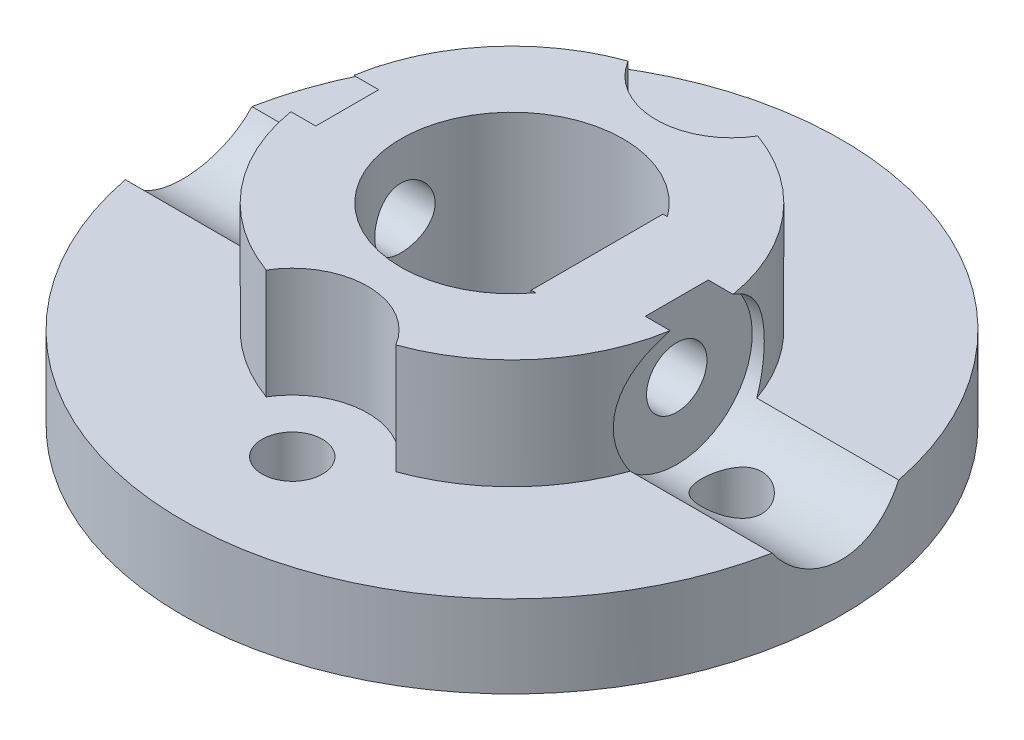
SolidWorks part; units mm, degrees
ref_plane "Front Plane" through (0, 0, 0) normal (0, 0, 1) x (1, 0, 0)
ref_plane "Top Plane" through (0, 0, 0) normal (0, 1, 0) x (1, 0, 0)
ref_plane "Right Plane" through (0, 0, 0) normal (1, 0, 0) x (0, 0, -1)
sketch "Stock_horn_drive_flange_profile" plane through (0, 0, 0) normal (0, 1, 0) x (1, 0, 0)
  circle A0 centre (0, 0) radius 12
  circle A1 centre (0, 0) radius 4.05
  dimension "D1" = 24
  dimension "D2" = 8.1
extrude "Stock_horn_drive_flange" add sketch "Stock_horn_drive_flange_profile" along normal blind 3 from offset 41
sketch "D_coupling_ring_profile" plane through (0, 0, 0) normal (0, 1, 0) x (1, 0, 0)
  circle A0 centre (0, 0) radius 7
  circle A1 centre (0, 0) radius 4.05
  dimension "D1" = 14
  dimension "D2" = 8.1
extrude "D_coupling_ring" add sketch "D_coupling_ring_profile" along normal blind 4 from offset 44
sketch "D_key_land_profile" plane through (0, 0, 0) normal (0, 1, 0) x (1, 0, 0)
  line L1 (3.1, -2.4) -> (6, -2.4)
  line L2 (3.1, -2.4) -> (3.1, 2.4)
  line L3 (3.1, 2.4) -> (6, 2.4)
  line L4 (6, -2.4) -> (6, 2.4)
  dimension "D1" = 2.9
  dimension "D2" = 4.8
extrude "D_key_land" add sketch "D_key_land_profile" along normal blind 4 from offset 44
sketch "Stock_horn_screws_profile" plane through (0, 0, 0) normal (0, 1, 0) x (1, 0, 0)
  circle A0 centre (-8, 0) radius 1.1
  circle A1 centre (8, 0) radius 1.1
  circle A2 centre (0, -8) radius 1.1
  circle A3 centre (0, 8) radius 1.1
  dimension "D1" = 2.2
  dimension "D2" = 2.2
  dimension "D3" = 2.2
  dimension "D4" = 2.2
extrude "Stock_horn_screws" cut sketch "Stock_horn_screws_profile" along normal through all from offset 39
sketch "Two_horn_washer_clearances_profile" plane through (0, 0, 0) normal (0, 1, 0) x (1, 0, 0)
  circle A0 centre (0, -8) radius 2.75
  circle A1 centre (0, 8) radius 2.75
  dimension "D1" = 5.5
  dimension "D2" = 5.5
extrude "Two_horn_washer_clearances" cut sketch "Two_horn_washer_clearances_profile" along normal blind 4 from offset 44
sketch "Yaw_positive_retention_crossbolt_profile" plane through (0, 0, 0) normal (1, 0, 0) x (0, 0, -1)
  circle A0 centre (0, 45.5) radius 1.1
  dimension "D1" = 2.2
extrude "Yaw_positive_retention_crossbolt" cut sketch "Yaw_positive_retention_crossbolt_profile" along normal through all from offset 10
sketch "Crossbolt_flat_seat_-12" plane through (0, 0, 0) normal (1, 0, 0) x (0, 0, -1)
  circle A0 centre (0, 45.5) radius 2.75
  dimension "D1" = 5.5
extrude "Crossbolt_flat_seat_cut_-12" cut sketch "Crossbolt_flat_seat_-12" along normal blind 6 from offset 12
sketch "Crossbolt_flat_seat_6" plane through (0, 0, 0) normal (1, 0, 0) x (0, 0, -1)
  circle A0 centre (0, 45.5) radius 2.75
  dimension "D1" = 5.5
extrude "Crossbolt_flat_seat_cut_6" cut sketch "Crossbolt_flat_seat_6" along normal blind 6 from offset 6
